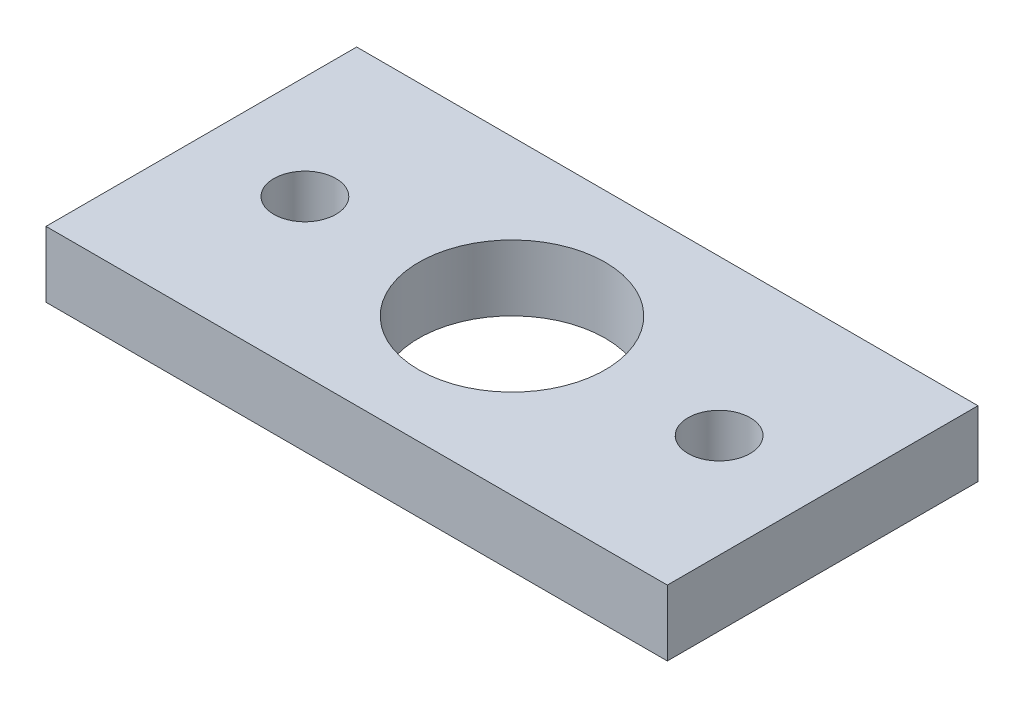
SolidWorks part; units mm, degrees
ref_plane "Front" through (0, 0, 0) normal (0, 0, 1) x (1, 0, 0)
ref_plane "Top" through (0, 0, 0) normal (0, 1, 0) x (1, 0, 0)
ref_plane "Right" through (0, 0, 0) normal (1, 0, 0) x (0, 0, -1)
sketch "Sketch1" plane through (0, 0, 0) normal (0, 1, 0) x (1, 0, 0)
  line L0 (15, 7.5) -> (25, 7.5)
  line L1 (0, 0) -> (30, 0)
  line L2 (0, 0) -> (0, 15)
  line L3 (0, 15) -> (30, 15)
  line L4 (30, 0) -> (30, 15)
  line L5 (15, 7.5) -> (5, 7.5)
  circle A0 centre (15, 7.5) radius 4.5
  circle A1 centre (25, 7.5) radius 1.5
  circle A2 centre (5, 7.5) radius 1.5
  dimension "D3" = 10
  dimension "D4" = 10
  dimension "D1" = 15
  dimension "D2" = 30
extrude "Boss-Extrude2" add sketch "Sketch1" along normal blind 3.175
